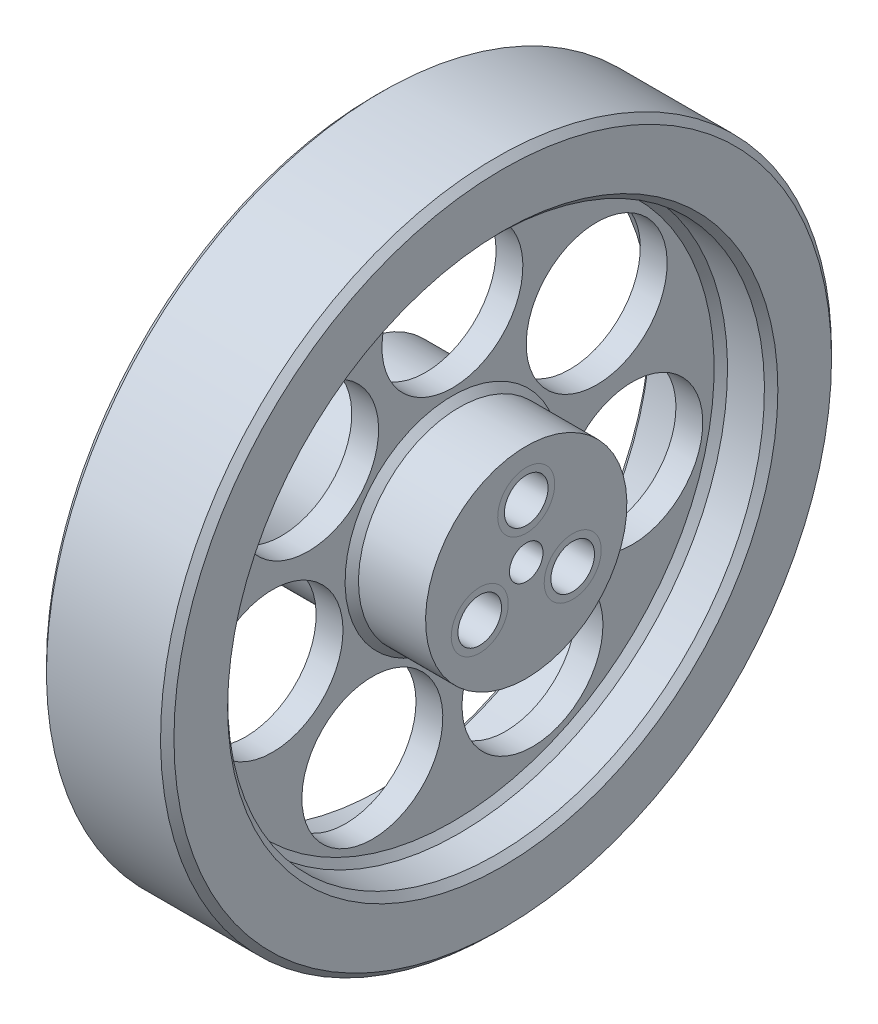
SolidWorks part; units mm, degrees
ref_plane "Ön Düzlem" through (0, 0, 0) normal (0, 0, 1) x (1, 0, 0)
ref_plane "Üst Düzlem" through (0, 0, 0) normal (0, 1, 0) x (1, 0, 0)
ref_plane "Sağ Düzlem" through (0, 0, 0) normal (1, 0, 0) x (0, 0, -1)
sketch "Çizim1" plane through (0, 0, 0) normal (0, 0, 1) x (1, 0, 0)
  line L0 (-13, 2.5) -> (13, 2.5)
  line L1 (-43.2592, 0) -> (43.2592, 0) construction
  line L2 (-13, 2.5) -> (-13, 15)
  line L3 (-13, 15) -> (-2, 15)
  line L4 (-2, 15) -> (-2, 40)
  line L5 (-2, 40) -> (-9.5, 40)
  line L6 (-9.5, 40) -> (-9.5, 50)
  line L7 (0, 0) -> (0, -9.9693) construction
  line L8 (13, 2.5) -> (13, 15)
  line L9 (9.5, 40) -> (9.5, 50)
  line L10 (2, 40) -> (9.5, 40)
  line L11 (13, 15) -> (2, 15)
  line L12 (2, 15) -> (2, 40)
  line L13 (-9.5, 50) -> (9.5, 50)
  point P6 (0, 0)
  point P8 (0, 2.5)
  dimension "D1" = 26
  dimension "D2" = 2.5
  dimension "D3" = 15
  dimension "D4" = 2
  dimension "D5" = 40
  dimension "D6" = 7.5
  dimension "D7" = 50
revolve "Döndür1" add sketch "Çizim1" angle 360 about L1
chamfer "Pah1" distance 1 angle 45 8 edges at (2, -15, 0) (-2, -40, 0) (-9.5, -40, 0) (9.5, -40, 0) (-9.5, -50, 0) (9.5, -50, 0) (-2, -15, 0) (2, -40, 0)
sketch "Çizim2" plane through (-2, 0, 0) normal (-1, 0, 0) x (0, 0, 1)
  circle A0 centre (0, 0) radius 27.5 construction
  circle A1 centre (0, 27.5) radius 10.5
  circle A2 centre (21.5004, 17.146) radius 10.5
  circle A3 centre (26.8105, -6.1193) radius 10.5
  circle A4 centre (11.9318, -24.7766) radius 10.5
  circle A5 centre (-11.9318, -24.7766) radius 10.5
  circle A6 centre (-26.8105, -6.1193) radius 10.5
  circle A7 centre (-21.5004, 17.146) radius 10.5
  point P6 (0, 0)
  point P7 (116.4103, -23.8192)
  point P19 (0, 0)
  dimension "D1" = 55
  dimension "D2" = 21
  dimension "D3" = 7
extrude "Kes-Ekstrüzyon1" cut sketch "Çizim2" against normal through all
sketch "Çizim3" plane through (13, 0, 0) normal (1, 0, 0) x (0, 0, -1)
  circle A0 centre (0, 0) radius 8 construction
  circle A1 centre (0, 8) radius 4.25
  circle A2 centre (6.9282, -4) radius 4.25
  circle A3 centre (-6.9282, -4) radius 4.25
  point P5 (9.0594, -5.2022)
  point P12 (0, 0)
  dimension "D1" = 16
  dimension "D2" = 8.5
  dimension "D3" = 3
extrude "Kes-Ekstrüzyon2" cut sketch "Çizim3" against normal through all
sketch "Çizim4" plane through (13, 0, 0) normal (1, 0, 0) x (0, 0, -1)
  line L0 (-4.25, 8) -> (-3.25, 8)
  circle A0 centre (0, 8) radius 3.25
  circle A1 centre (-6.9282, -4) radius 4.25
  circle A2 centre (-6.9282, -4) radius 4.25
  circle A3 centre (6.9282, -4) radius 4.25
  circle A4 centre (6.9282, -4) radius 4.25
  circle A5 centre (0, 8) radius 4.25
  circle A6 centre (0, 8) radius 4.25
  circle A7 centre (6.9282, -4) radius 3.25
  circle A8 centre (-6.9282, -4) radius 3.25
  dimension "D1" = 0
  dimension "D2" = 0
  dimension "D3" = 0
  dimension "D4" = 1
extrude "Yükseklik-Ekstrüzyon2" add sketch "Çizim4" against normal through all separate body
